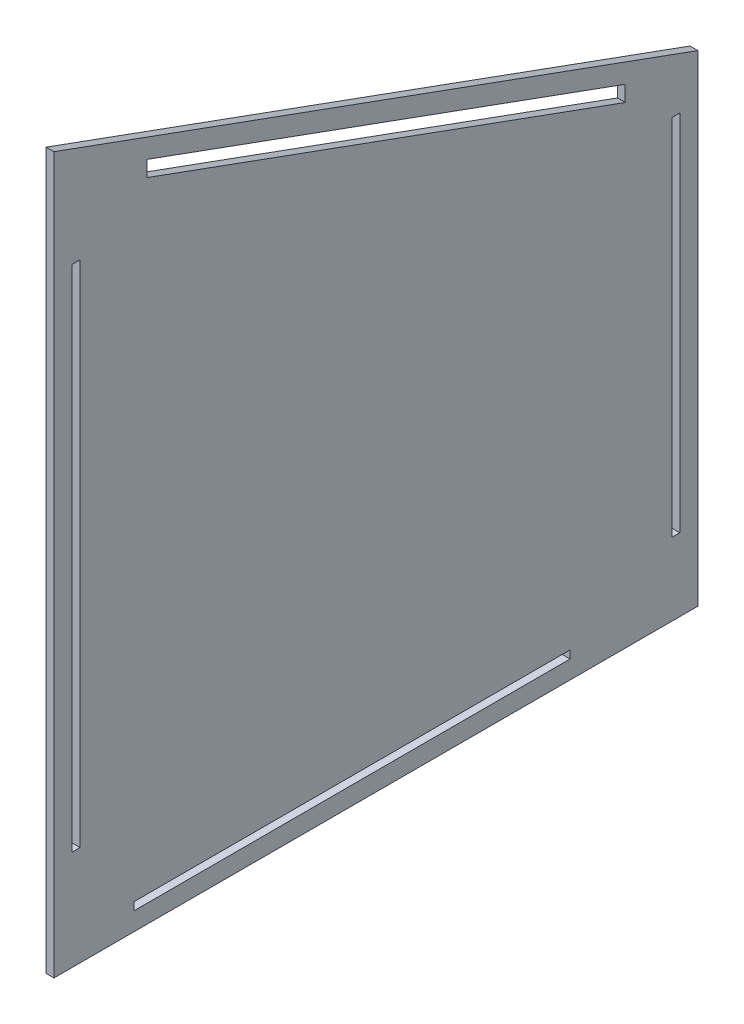
SolidWorks part; units mm, degrees
ref_plane "Alzado" through (0, 0, 0) normal (0, 0, 1) x (1, 0, 0)
ref_plane "Planta" through (0, 0, 0) normal (0, 1, 0) x (1, 0, 0)
ref_plane "Vista lateral" through (0, 0, 0) normal (1, 0, 0) x (0, 0, -1)
sketch "Croquis1" plane through (0, 0, 0) normal (1, 0, 0) x (0, 0, -1)
  line L0 (450, 0) -> (0, 0)
  line L1 (0, 0) -> (0, 500)
  line L2 (0, 500) -> (450, 336.2134)
  line L3 (450, 336.2134) -> (450, 0)
  line L5 (65.0453, 462.8104) -> (399.2, 341.188)
  line L6 (65.0453, 462.8104) -> (65.0453, 451.8104)
  line L7 (65.0453, 451.8104) -> (399.2, 330.188)
  line L8 (399.2, 341.188) -> (399.2, 330.188)
  line L9 (55.88, 12.7) -> (360.68, 12.7)
  line L10 (55.88, 12.7) -> (55.88, 18.2)
  line L11 (55.88, 18.2) -> (360.68, 18.2)
  line L12 (360.68, 12.7) -> (360.68, 18.2)
  line L13 (12.7, 425.45) -> (18.2, 425.45)
  line L14 (12.7, 425.45) -> (12.7, 69.85)
  line L15 (12.7, 69.85) -> (18.2, 69.85)
  line L16 (18.2, 425.45) -> (18.2, 69.85)
  line L17 (431.8, 304.8) -> (437.3, 304.8)
  line L18 (431.8, 304.8) -> (431.8, 50.8)
  line L19 (431.8, 50.8) -> (437.3, 50.8)
  line L20 (437.3, 304.8) -> (437.3, 50.8)
  dimension "D1" = 70
  dimension "D2" = 500
  dimension "D3" = 450
  dimension "D4" = 355.6
  dimension "D5" = 11
  dimension "D6" = 50.8
  dimension "D7" = 5.5
  dimension "D8" = 304.8
  dimension "D9" = 55.88
  dimension "D10" = 12.7
  dimension "D11" = 12.7
  dimension "D12" = 5.5
  dimension "D13" = 355.6
  dimension "D14" = 69.85
  dimension "D15" = 12.7
  dimension "D16" = 5.5
  dimension "D17" = 254
  dimension "D18" = 50.8
  dimension "D19" = 12.7
extrude "Saliente-Extruir1" add sketch "Croquis1" along normal mid plane 5.5
sketch "Croquis2" [suppressed] plane through (0, 0, 0) normal (0, 1, 0) x (1, 0, 0)
  line L0 (71.1556, 481.5299) -> (71.1556, 125.9299)
  line L1 (71.1556, 125.9299) -> (96.5556, 125.9299)
  line L2 (96.5556, 125.9299) -> (96.5556, 95.9299)
  line L3 (96.5556, 95.9299) -> (419.4133, 95.9299)
  line L4 (419.4133, 95.9299) -> (419.4133, 125.9299)
  line L5 (419.4133, 125.9299) -> (444.8133, 125.9299)
  line L6 (444.8133, 125.9299) -> (444.8133, 481.5299)
  line L7 (444.8133, 481.5299) -> (419.4133, 481.5299)
  line L8 (419.4133, 481.5299) -> (419.4133, 511.5299)
  line L9 (419.4133, 511.5299) -> (96.5556, 511.5299)
  line L10 (96.5556, 511.5299) -> (96.5556, 481.5299)
  line L11 (96.5556, 481.5299) -> (71.1556, 481.5299)
  dimension "D1" = 355.6
  dimension "D2" = 25.4
  dimension "D3" = 30
delete or keep bodies "Sólido-Eliminar/Conservar 2" [suppressed] type keep bodies bodies 101
extrude "Saliente-Extruir3" [suppressed] add sketch "Croquis2" along normal blind 5.5 separate body
delete or keep bodies "Sólido-Eliminar/Conservar 3" [suppressed] type keep bodies bodies 103
